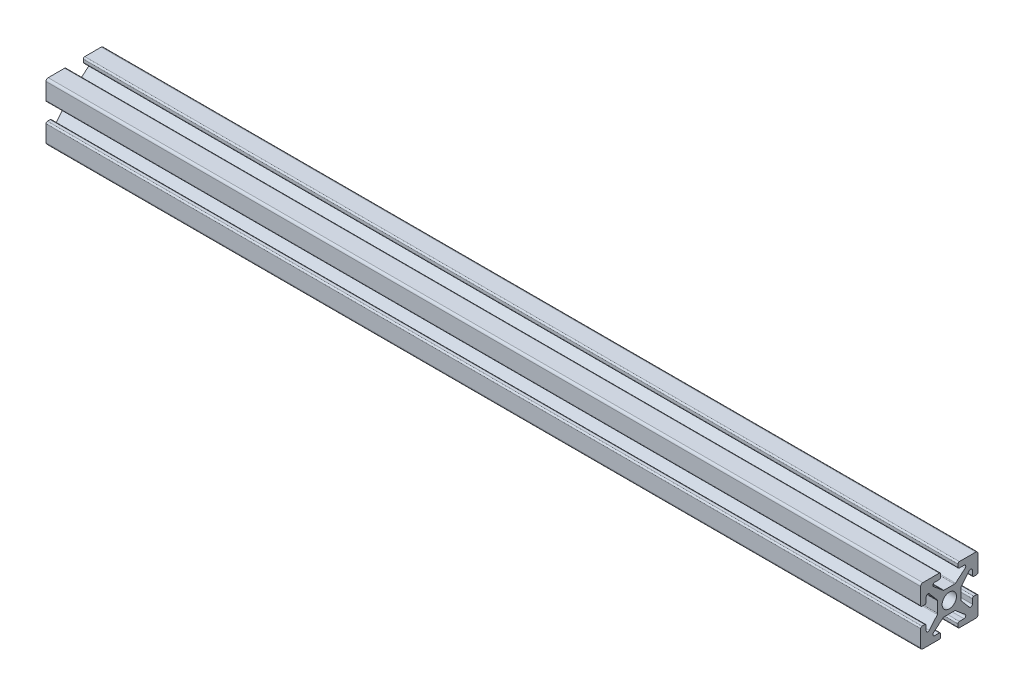
SolidWorks part; units mm, degrees
ref_plane "Front Plane" through (0, 0, 0) normal (0, 0, 1) x (1, 0, 0)
ref_plane "Top Plane" through (0, 0, 0) normal (0, 1, 0) x (1, 0, 0)
ref_plane "Right Plane" through (0, 0, 0) normal (1, 0, 0) x (0, 0, -1)
sketch "Sketch1" plane through (0, 0, 0) normal (1, 0, 0) x (0, 0, -1)
  line L0 (0, 5) -> (0, -5) construction
  line L1 (-5, 5) -> (5, 5)
  line L2 (-5, 5) -> (-5, -5)
  line L3 (-5, -5) -> (5, -5)
  line L4 (5, 5) -> (5, -5)
  line L5 (-5, 0) -> (5, 0) construction
  line L6 (-1.019, 2.0193) -> (1.019, 2.0193)
  line L7 (1.019, 2.0193) -> (2.7598, 3.4799)
  line L8 (2.8702, 3.7168) -> (-2.8702, 3.7168) construction
  circle A0 centre (0, 0) radius 1.2573
  arc A1 (2.7598, 3.4799) -> (2.5611, 4.0259) centre (2.5611, 3.7168) ccw
  arc A2 (4.619, 5) -> (5, 4.619) centre (4.619, 4.619) cw
  point P8 (0, 0)
  point P10 (1.4986, 5)
  point P17 (0, 2.0193)
  point P19 (0, 1.2573)
  point P20 (-1.4986, 5)
  point P27 (1.4948, 5)
  dimension "D1" = 2.5146
  dimension "D5" = 0.381
  dimension "Rail Width" = 10
  dimension "Rail Height" = 10
  dimension "T-Slot Width" = 2.9972
  dimension "D2" = 0.762
  dimension "D3" = 2.0066
  dimension "D4" = 5.7404
  dimension "D6" = 3.5052
  dimension "D7" = 40
  dimension "D8" = 2.0381
sketch "Sketch2" plane through (0, 0, 0) normal (0, 0, 1) x (1, 0, 0)
  line L0 (-76.2, 0) -> (76.2, 0)
  line L1 (-76.2, 5) -> (76.2, 5) construction
  point P0 (-61.2, 0)
  point P4 (0, 0)
  point P5 (61.2, 0)
  dimension "Length" = 152.4
  dimension "D1" = 15
  dimension "D2" = 15
sketch "Sketch4" plane through (0, 0, 0) normal (1, 0, 0) x (0, 0, -1)
  line L0 (-5, 0) -> (5, 0) construction
  line L1 (0, 1.2573) -> (0, 2.0193)
  line L2 (0, 2.0193) -> (0.9266, 2.0193)
  line L3 (1.0899, 2.0787) -> (2.7598, 3.4799)
  line L4 (2.5611, 4.0259) -> (1.7526, 4.0259)
  line L5 (1.4986, 4.2799) -> (1.4986, 4.746)
  line L6 (1.7526, 5) -> (4.619, 5)
  line L7 (0, 0) -> (5, 5) construction
  line L9 (5, 1.7526) -> (5, 4.619)
  line L10 (4.2799, 1.4986) -> (4.746, 1.4986)
  line L11 (4.0259, 2.5611) -> (4.0259, 1.7526)
  line L12 (2.0787, 1.0899) -> (3.4799, 2.7598)
  line L13 (2.0193, 0) -> (2.0193, 0.9266)
  line L14 (1.2573, 0) -> (2.0193, 0)
  arc A0 (0, 1.2573) -> (1.2573, 0) centre (0, 0) cw
  circle A1 centre (0, 0) radius 1.2573 construction
  arc A2 (2.7598, 3.4799) -> (2.5611, 4.0259) centre (2.5611, 3.7168) ccw construction
  arc A3 (2.7598, 3.4799) -> (2.5611, 4.0259) centre (2.5611, 3.7168) ccw
  arc A4 (5, 4.619) -> (4.619, 5) centre (4.619, 4.619) ccw construction
  arc A5 (5, 4.619) -> (4.619, 5) centre (4.619, 4.619) ccw
  arc A6 (0.9266, 2.0193) -> (1.0899, 2.0787) centre (0.9266, 2.2733) ccw
  arc A7 (1.7526, 5) -> (1.4986, 4.746) centre (1.7526, 4.746) ccw
  arc A8 (1.4986, 4.2799) -> (1.7526, 4.0259) centre (1.7526, 4.2799) ccw
  arc A9 (5, 1.7526) -> (4.746, 1.4986) centre (4.746, 1.7526) cw
  arc A10 (4.2799, 1.4986) -> (4.0259, 1.7526) centre (4.2799, 1.7526) cw
  arc A11 (3.4799, 2.7598) -> (4.0259, 2.5611) centre (3.7168, 2.5611) cw
  arc A12 (2.0193, 0.9266) -> (2.0787, 1.0899) centre (2.2733, 0.9266) cw
  point P26 (1.019, 2.0193)
  point P30 (1.4986, 5)
  dimension "D1" = 0.254
extrude "Boss-Extrude1" add sketch "Sketch4" along normal up to vertex (76.2 mm away) from vertex at -76.2 starting at point (-76.2, 0, 0)
mirror "Mirror1" about plane through (0, 0, 0) normal (0, 1, 0) of bodies 104
mirror "Mirror2" about plane through (0, 0, 0) normal (0, 0, 1) of bodies 105
equation "\"D8@Sketch1\"=\"T-Slot Width@Sketch1\"*.68"
equation "\"D1@Sketch2\"=\"Rail Width@Sketch1\"*1.5"
equation "\"D2@Sketch2\"=\"D1@Sketch2\""
